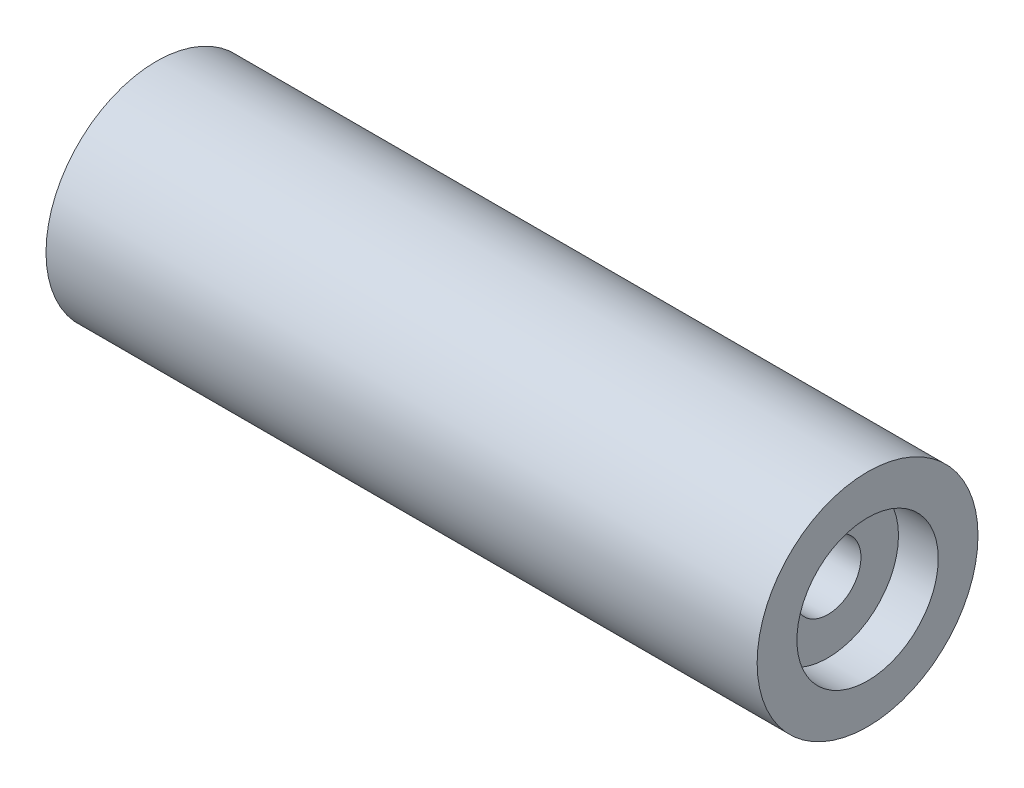
SolidWorks part; units mm, degrees
material "AISI 304"
ref_plane "Ön Düzlem" through (0, 0, 0) normal (0, 0, 1) x (1, 0, 0)
ref_plane "Üst Düzlem" through (0, 0, 0) normal (0, 1, 0) x (1, 0, 0)
ref_plane "Sağ Düzlem" through (0, 0, 0) normal (1, 0, 0) x (0, 0, -1)
sketch "Çizim1" plane through (0, 0, 0) normal (1, 0, 0) x (0, 0, -1)
  circle A0 centre (0, 0) radius 25
  circle A1 centre (0, 0) radius 7.5
  dimension "D1" = 50
  dimension "D2" = 15
extrude "Yükseklik-Ekstrüzyon1" add sketch "Çizim1" along normal mid plane 161
sketch "Çizim2" plane through (80.5, 0, 0) normal (1, 0, 0) x (0, 0, -1)
  circle A0 centre (0, 0) radius 16
extrude "Kes-Ekstrüzyon1" cut sketch "Çizim2" against normal blind 9
mirror "Aynalama1" about plane through (0, 0, 0) normal (1, 0, 0) of "Kes-Ekstrüzyon1"
